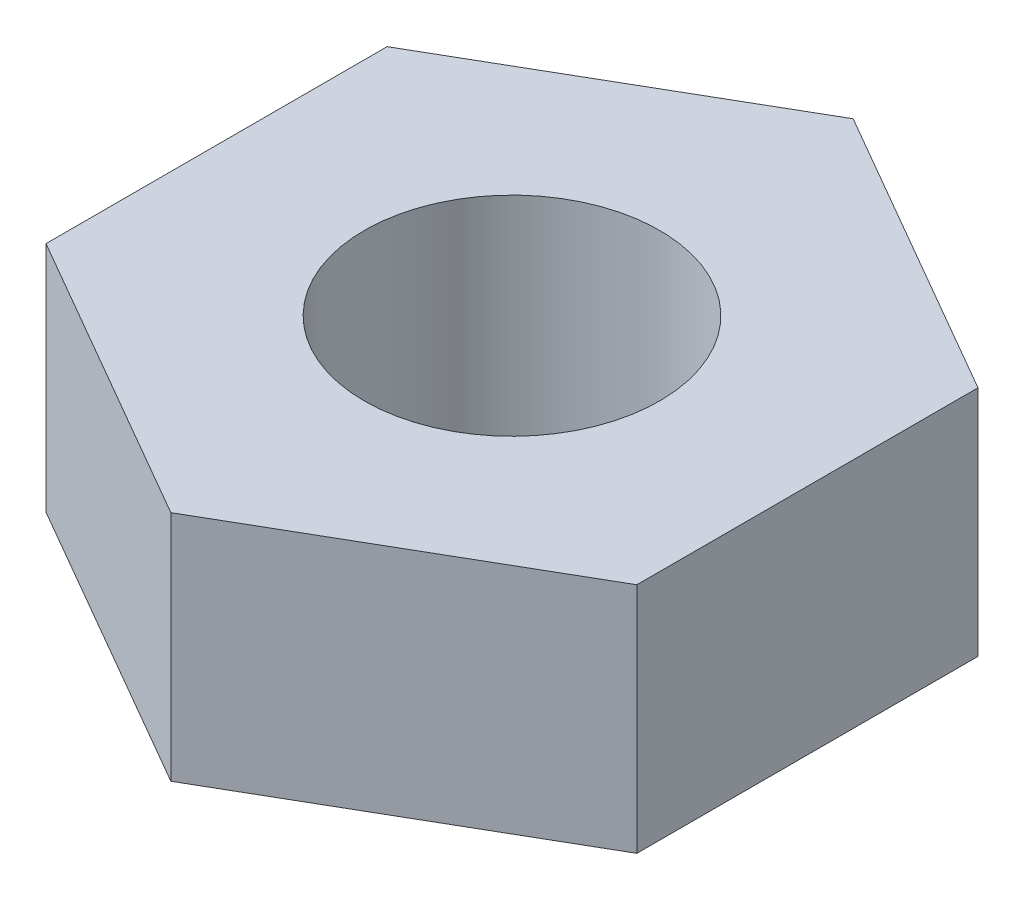
SolidWorks part; units mm, degrees
ref_plane "Front Plane" through (0, 0, 0) normal (0, 0, 1) x (1, 0, 0)
ref_plane "Top Plane" through (0, 0, 0) normal (0, 1, 0) x (1, 0, 0)
ref_plane "Right Plane" through (0, 0, 0) normal (1, 0, 0) x (0, 0, -1)
sketch "Sketch2" plane through (0, 0, 0) normal (0, 1, 0) x (1, 0, 0)
  line L1 (12.7, 7.3323) -> (0, 14.6647)
  line L2 (0, 14.6647) -> (-12.7, 7.3323)
  line L3 (-12.7, 7.3323) -> (-12.7, -7.3323)
  line L4 (-12.7, -7.3323) -> (0, -14.6647)
  line L5 (0, -14.6647) -> (12.7, -7.3323)
  line L6 (12.7, -7.3323) -> (12.7, 7.3323)
  circle A0 centre (0, 0) radius 12.7 construction
  dimension "D1" = 25.4
extrude "Boss-Extrude1" add sketch "Sketch2" along normal mid plane 10
sketch "Sketch3" plane through (0, 5, 0) normal (0, 1, 0) x (1, 0, 0)
  circle A0 centre (0, 0) radius 6.35
extrude "Cut-Extrude1" cut sketch "Sketch3" against normal through all
cosmetic thread "Cosmetic Thread1" parameters "D2"=15.875
sketch "Sketch4" plane through (0, -5, 0) normal (0, -1, 0) x (1, 0, 0)
  circle A1 centre (0, 0) radius 12.7
